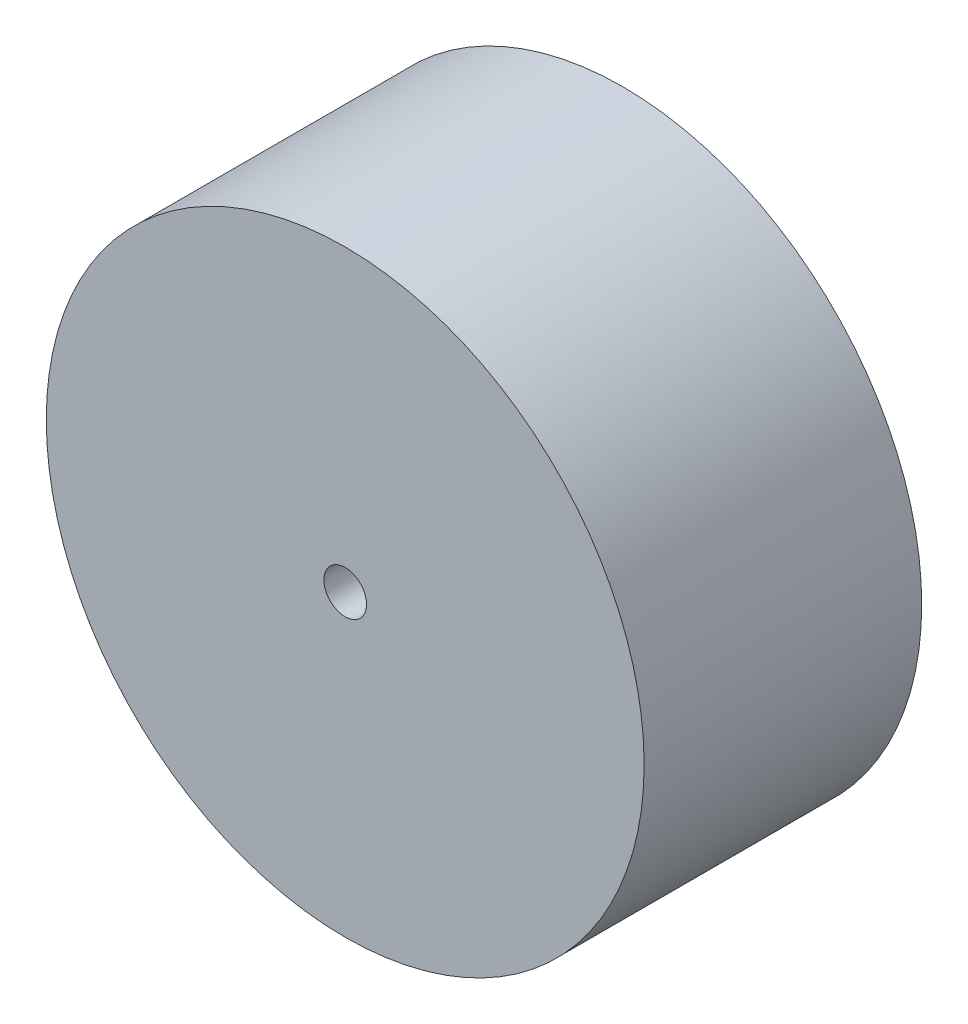
SolidWorks part; units mm, degrees
ref_plane "Front Plane" through (0, 0, 0) normal (0, 0, 1) x (1, 0, 0)
ref_plane "Top Plane" through (0, 0, 0) normal (0, 1, 0) x (1, 0, 0)
ref_plane "Right Plane" through (0, 0, 0) normal (1, 0, 0) x (0, 0, -1)
sketch "Sketch1" plane through (0, 0, 0) normal (0, 0, 1) x (1, 0, 0)
  circle A0 centre (0, 0) radius 28
  dimension "D1" = 56
extrude "Boss-Extrude1" add sketch "Sketch1" along normal blind 26
sketch "Sketch2" plane through (0, 0, 26) normal (0, 0, 1) x (1, 0, 0)
  circle A0 centre (0, 0) radius 2
  dimension "D1" = 4
extrude "Cut-Extrude1" cut sketch "Sketch2" against normal blind 26
